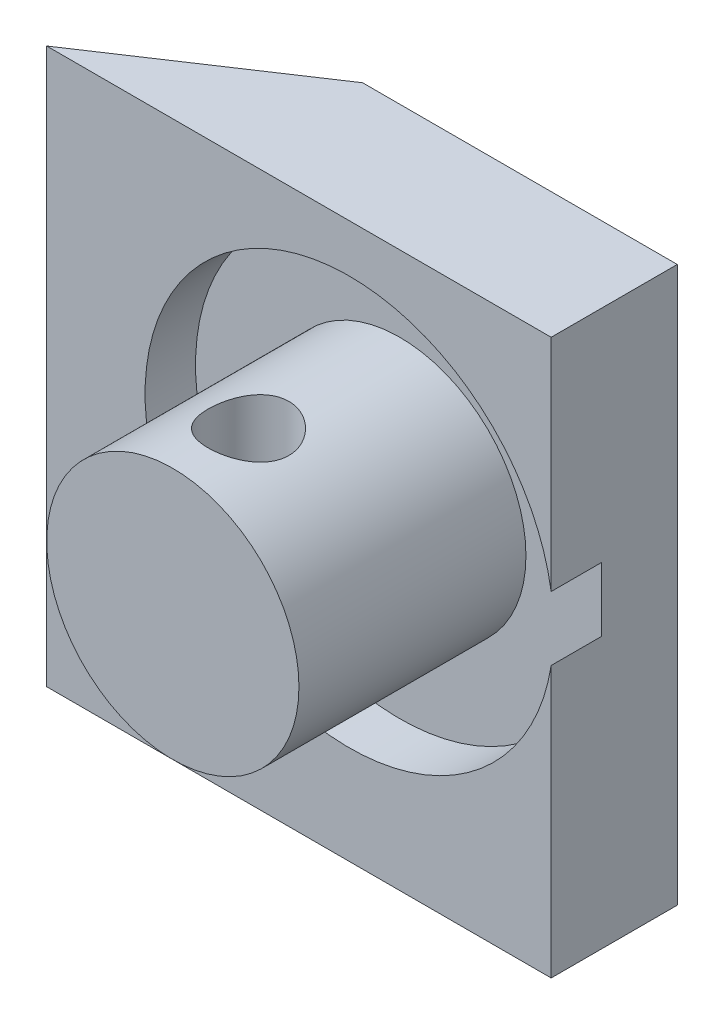
SolidWorks part; units mm, degrees
ref_plane "前视基准面" through (0, 0, 0) normal (0, 0, 1) x (1, 0, 0)
ref_plane "上视基准面" through (0, 0, 0) normal (0, 1, 0) x (1, 0, 0)
ref_plane "右视基准面" through (0, 0, 0) normal (1, 0, 0) x (0, 0, -1)
sketch "草图1" plane through (0, 0, 0) normal (0, 1, 0) x (1, 0, 0)
  line L0 (0, 0) -> (-20, 0)
  line L1 (-20, 0) -> (-12.4775, 5)
  line L2 (0, 5) -> (0, 0)
  line L3 (0, 5) -> (-12.4775, 5)
  point P4 (-20, -0.7411)
  dimension "D1" = 33.611
  dimension "D2" = 20
  dimension "D4" = 5
extrude "凸台-拉伸1" add sketch "草图1" along normal blind 22
sketch "草图2" plane through (0, 0, 0) normal (0, 0, 1) x (1, 0, 0)
  line L0 (-20, 22) -> (-20, 0) construction
  line L1 (-20, 22) -> (0, 22) construction
  circle A0 centre (-8, 12) radius 5
  dimension "D1" = 10
  dimension "D2" = 12
  dimension "D3" = 10
extrude "凸台-拉伸2" add sketch "草图2" along normal blind 7
sketch "草图3" plane through (0, 0, 0) normal (0, 0, 1) x (1, 0, 0)
  circle A0 centre (-8, 12) radius 5
  circle A1 centre (-8, 12) radius 8.1
  dimension "D1" = 10
  dimension "D2" = 16.2
extrude "切除-拉伸1" cut sketch "草图3" against normal blind 2
sketch "草图4" plane through (0, 0, 0) normal (0, 1, 0) x (1, 0, 0)
  line L0 (-13, -7) -> (-3, -7) construction
  line L1 (-13, 2) -> (-13, -7) construction
  circle A0 centre (-8, -4) radius 1.6
  point P4 (-7.5139, -4.4257)
  dimension "D1" = 3
  dimension "D2" = 3.2
  dimension "D3" = 5
extrude "切除-拉伸2" cut sketch "草图4" along normal through all
